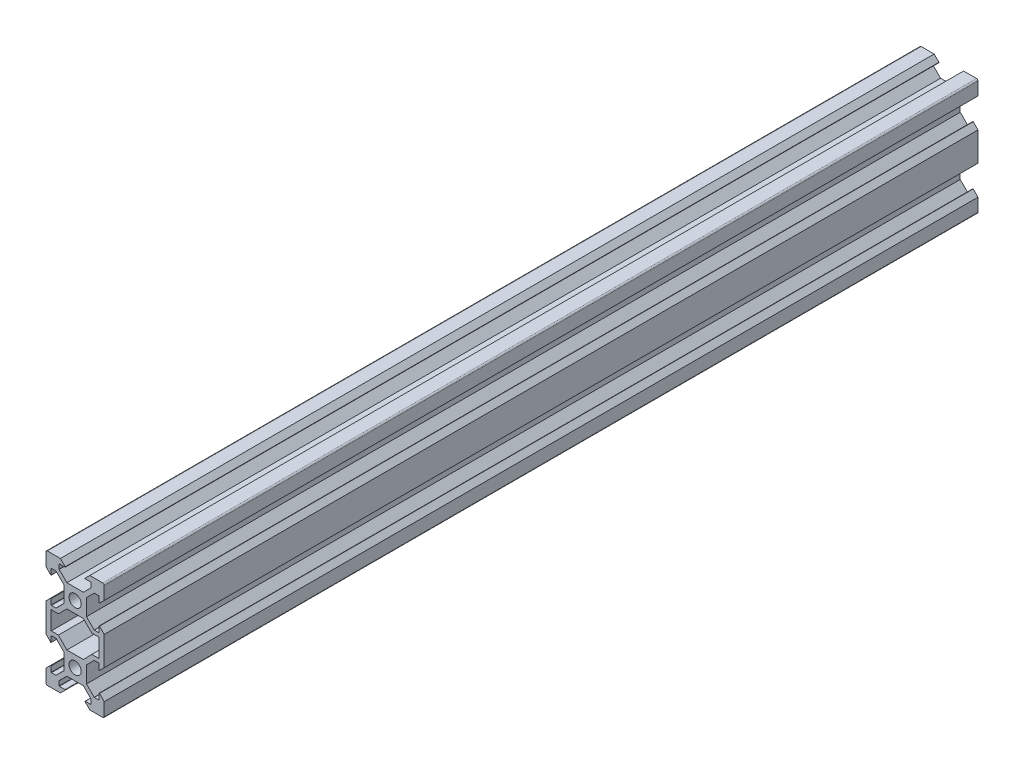
SolidWorks part; units mm, degrees
ref_plane "Front Plane" through (0, 0, 0) normal (0, 0, 1) x (1, 0, 0)
ref_plane "Top Plane" through (0, 0, 0) normal (0, 1, 0) x (1, 0, 0)
ref_plane "Right Plane" through (0, 0, 0) normal (1, 0, 0) x (0, 0, -1)
sketch "Sketch1" plane through (0, 0, 0) normal (0, 0, 1) x (1, 0, 0)
  line L0 (0, 0) -> (-29.3691, 0) construction
  line L1 (9.5, 20) -> (5.0492, 20)
  line L2 (10, 19.5) -> (10, 15.0492)
  line L3 (9.5, -20) -> (-9.5, -20)
  line L4 (-10, 19.5) -> (-10, 15.0492)
  line L5 (9.9, 19.8) -> (-9.9, -19.8) construction
  line L6 (9.9, -19.8) -> (-9.9, 19.8) construction
  line L7 (0, 0) -> (0, 13.9) construction
  line L8 (-5.0492, 20) -> (-3.4199, 18.3707)
  line L9 (-3.4906, 18.2) -> (-5.4, 18.2)
  line L10 (-5.5, 18.1) -> (-5.5, 16.6021)
  line L11 (-5.4707, 16.5314) -> (-2.8393, 13.9)
  line L12 (-2.8393, 13.9) -> (2.8393, 13.9)
  line L13 (-9.8536, 19.8536) -> (10, 0) construction
  line L15 (-3.9, 12.8393) -> (-3.9, 7.1607)
  line L16 (-6.5314, 15.4707) -> (-3.9, 12.8393)
  line L17 (-8.1, 15.5) -> (-6.6021, 15.5)
  line L18 (-8.2, 13.4906) -> (-8.2, 15.4)
  line L19 (-10, 15.0492) -> (-8.3707, 13.4199)
  line L20 (10, 15.0492) -> (8.3707, 13.4199)
  line L21 (8.2, 13.4906) -> (8.2, 15.4)
  line L22 (8.1, 15.5) -> (6.6021, 15.5)
  line L23 (6.5314, 15.4707) -> (3.9, 12.8393)
  line L24 (3.9, 12.8393) -> (3.9, 7.1607)
  line L25 (5.4707, 16.5314) -> (2.8393, 13.9)
  line L26 (5.5, 18.1) -> (5.5, 16.6021)
  line L27 (3.4906, 18.2) -> (5.4, 18.2)
  line L28 (5.0492, 20) -> (3.4199, 18.3707)
  line L29 (5.0492, -20) -> (3.4199, -18.3707)
  line L30 (3.4906, -18.2) -> (5.4, -18.2)
  line L31 (5.5, -18.1) -> (5.5, -16.6021)
  line L32 (5.4707, -16.5314) -> (2.8393, -13.9)
  line L33 (3.9, -12.8393) -> (3.9, -10)
  line L34 (6.5314, -15.4707) -> (3.9, -12.8393)
  line L35 (8.1, -15.5) -> (6.6021, -15.5)
  line L36 (8.2, -13.4906) -> (8.2, -15.4)
  line L37 (10, -15.0492) -> (8.3707, -13.4199)
  line L38 (-10, -15.0492) -> (-8.3707, -13.4199)
  line L39 (-8.2, -13.4906) -> (-8.2, -15.4)
  line L40 (-8.1, -15.5) -> (-6.6021, -15.5)
  line L41 (-6.5314, -15.4707) -> (-3.9, -12.8393)
  line L42 (-3.9, -12.8393) -> (-3.9, -10)
  line L43 (-2.8393, -13.9) -> (2.8393, -13.9)
  line L44 (-5.4707, -16.5314) -> (-2.8393, -13.9)
  line L45 (-5.5, -18.1) -> (-5.5, -16.6021)
  line L46 (-3.4906, -18.2) -> (-5.4, -18.2)
  line L47 (-5.0492, -20) -> (-3.4199, -18.3707)
  line L48 (9.5, -20) -> (-9.5, -20)
  line L49 (10, 4.9508) -> (8.3707, 6.5801)
  line L50 (8.2, 6.5094) -> (8.2, 4.6)
  line L51 (8.1, 4.5) -> (6.6021, 4.5)
  line L52 (6.5314, 4.5293) -> (3.9, 7.1607)
  line L53 (-6.5314, 4.5293) -> (-3.9, 7.1607)
  line L54 (-8.1, 4.5) -> (-6.6021, 4.5)
  line L55 (-8.2, 6.5094) -> (-8.2, 4.6)
  line L56 (-10, 4.9508) -> (-8.3707, 6.5801)
  line L57 (10, -4.9508) -> (8.3707, -6.5801)
  line L58 (8.2, -6.5094) -> (8.2, -4.6)
  line L59 (8.1, -4.5) -> (6.6021, -4.5)
  line L60 (6.5314, -4.5293) -> (3.9, -7.1607)
  line L61 (3.9, -12.8393) -> (3.9, -7.1607)
  line L62 (-3.9, -12.8393) -> (-3.9, -7.1607)
  line L63 (-6.5314, -4.5293) -> (-3.9, -7.1607)
  line L64 (-8.1, -4.5) -> (-6.6021, -4.5)
  line L65 (-8.2, -6.5094) -> (-8.2, -4.6)
  line L66 (-10, -4.9508) -> (-8.3707, -6.5801)
  line L67 (-2.8393, 6.1) -> (2.8393, 6.1)
  line L68 (-2.8393, -6.1) -> (2.8393, -6.1)
  line L69 (-2.8393, 6.1) -> (-5.7353, 3.204)
  line L70 (-5.7353, 3.204) -> (-8.2, 3.204)
  line L71 (-8.2, 3.204) -> (-8.2, -3.1175)
  line L72 (-8.2, -3.1175) -> (-5.7353, -3.1175)
  line L73 (-5.7353, -3.1175) -> (-2.8393, -6.1)
  line L74 (5.7353, -3.1175) -> (2.8393, -6.1)
  line L75 (8.2, -3.1175) -> (5.7353, -3.1175)
  line L76 (8.2, 3.204) -> (8.2, -3.1175)
  line L77 (5.7353, 3.204) -> (8.2, 3.204)
  line L78 (2.8393, 6.1) -> (5.7353, 3.204)
  line L79 (-10, -15.0492) -> (-10, -19.5)
  line L80 (-10, 4.9508) -> (-10, -4.9508)
  line L81 (-5, 10) -> (5, 10) construction
  line L82 (-5.0492, 20) -> (-9.5, 20)
  line L83 (0, 20) -> (0, 23.0284) construction
  line L84 (10, 4.9508) -> (10, -4.9508)
  line L86 (10, -15.0492) -> (10, -19.5)
  arc A0 (-5.5, 16.6021) -> (-5.4707, 16.5314) centre (-5.4, 16.6021) ccw
  arc A1 (-5.4, 18.2) -> (-5.5, 18.1) centre (-5.4, 18.1) ccw
  arc A2 (-3.4199, 18.3707) -> (-3.4906, 18.2) centre (-3.4906, 18.3) cw
  arc A3 (-9.5, 20) -> (-10, 19.5) centre (-9.5, 19.5) ccw
  arc A4 (-6.6021, 15.5) -> (-6.5314, 15.4707) centre (-6.6021, 15.4) cw
  arc A5 (-8.2, 15.4) -> (-8.1, 15.5) centre (-8.1, 15.4) cw
  arc A6 (-8.3707, 13.4199) -> (-8.2, 13.4906) centre (-8.3, 13.4906) ccw
  arc A7 (8.3707, 13.4199) -> (8.2, 13.4906) centre (8.3, 13.4906) cw
  arc A8 (8.2, 15.4) -> (8.1, 15.5) centre (8.1, 15.4) ccw
  arc A9 (6.6021, 15.5) -> (6.5314, 15.4707) centre (6.6021, 15.4) ccw
  arc A10 (9.5, 20) -> (10, 19.5) centre (9.5, 19.5) cw
  arc A11 (3.4199, 18.3707) -> (3.4906, 18.2) centre (3.4906, 18.3) ccw
  arc A12 (5.4, 18.2) -> (5.5, 18.1) centre (5.4, 18.1) cw
  arc A13 (5.5, 16.6021) -> (5.4707, 16.5314) centre (5.4, 16.6021) cw
  arc A14 (5.5, -16.6021) -> (5.4707, -16.5314) centre (5.4, -16.6021) ccw
  arc A15 (5.4, -18.2) -> (5.5, -18.1) centre (5.4, -18.1) ccw
  arc A16 (3.4199, -18.3707) -> (3.4906, -18.2) centre (3.4906, -18.3) cw
  arc A17 (9.5, -20) -> (10, -19.5) centre (9.5, -19.5) ccw
  arc A18 (6.6021, -15.5) -> (6.5314, -15.4707) centre (6.6021, -15.4) cw
  arc A19 (8.2, -15.4) -> (8.1, -15.5) centre (8.1, -15.4) cw
  arc A20 (8.3707, -13.4199) -> (8.2, -13.4906) centre (8.3, -13.4906) ccw
  arc A21 (-8.3707, -13.4199) -> (-8.2, -13.4906) centre (-8.3, -13.4906) cw
  arc A22 (-8.2, -15.4) -> (-8.1, -15.5) centre (-8.1, -15.4) ccw
  arc A23 (-6.6021, -15.5) -> (-6.5314, -15.4707) centre (-6.6021, -15.4) ccw
  arc A24 (-9.5, -20) -> (-10, -19.5) centre (-9.5, -19.5) cw
  arc A25 (-3.4199, -18.3707) -> (-3.4906, -18.2) centre (-3.4906, -18.3) ccw
  arc A26 (-5.4, -18.2) -> (-5.5, -18.1) centre (-5.4, -18.1) cw
  arc A27 (-5.5, -16.6021) -> (-5.4707, -16.5314) centre (-5.4, -16.6021) cw
  arc A28 (8.3707, 6.5801) -> (8.2, 6.5094) centre (8.3, 6.5094) ccw
  arc A29 (8.2, 4.6) -> (8.1, 4.5) centre (8.1, 4.6) cw
  arc A30 (6.6021, 4.5) -> (6.5314, 4.5293) centre (6.6021, 4.6) cw
  arc A31 (-6.6021, 4.5) -> (-6.5314, 4.5293) centre (-6.6021, 4.6) ccw
  arc A32 (-8.2, 4.6) -> (-8.1, 4.5) centre (-8.1, 4.6) ccw
  arc A33 (-8.3707, 6.5801) -> (-8.2, 6.5094) centre (-8.3, 6.5094) cw
  arc A34 (8.3707, -6.5801) -> (8.2, -6.5094) centre (8.3, -6.5094) cw
  arc A35 (8.2, -4.6) -> (8.1, -4.5) centre (8.1, -4.6) ccw
  arc A36 (6.6021, -4.5) -> (6.5314, -4.5293) centre (6.6021, -4.6) ccw
  arc A37 (-6.6021, -4.5) -> (-6.5314, -4.5293) centre (-6.6021, -4.6) cw
  arc A38 (-8.2, -4.6) -> (-8.1, -4.5) centre (-8.1, -4.6) cw
  arc A39 (-8.3707, -6.5801) -> (-8.2, -6.5094) centre (-8.3, -6.5094) ccw
  circle A40 centre (0, 10) radius 2.1
  circle A41 centre (0, -10) radius 2.1
  point P0 (0, 0)
  point P23 (-3.2492, 18.2)
  point P65 (0, 13.9)
  point P66 (3.2492, 18.2)
  point P119 (3.2492, -18.2)
  point P120 (0, -13.9)
  point P121 (-3.2492, -18.2)
  point P133 (3.9, 10)
  point P134 (-3.9, 10)
  dimension "D8" = 0.1
  dimension "D9" = 0.5
  dimension "D10" = 4.2
  dimension "D2" = 45
  dimension "D3" = 3.2492
  dimension "D4" = 1.8
  dimension "D5" = 4.3
  dimension "D6" = 5.5
  dimension "D7" = 0.75
  dimension "D11" = 7.8
  dimension "D12" = 7.8
extrude "Boss-Extrude1" add sketch "Sketch1" along normal blind 300 contours L66 A39 L65 A38 L64 A37 L63 L62 L42 L41 A23 L40 A22 L39 A21 L38 L79 A24 L3 L47 A25 L46 A26 L45 A27 L44 L43 L32 A14 L31 A15 L30 A16 L29 A17 L86 L37 A20 L36 A19 L35 A18 L34 L33 L61 L60 A36 L59 A35 L58
